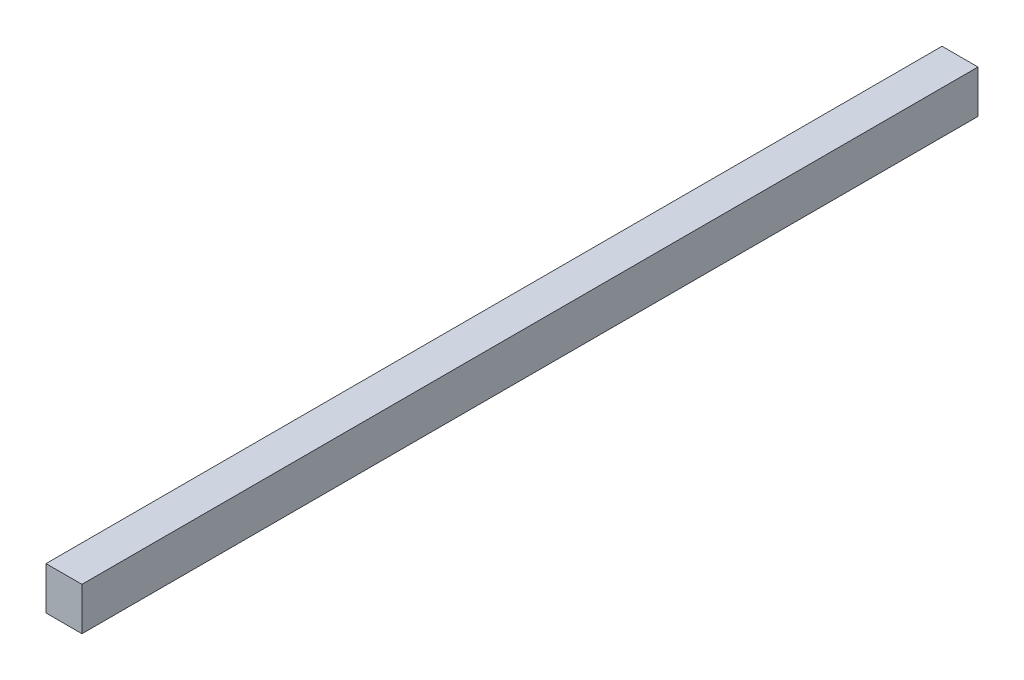
SolidWorks part; units mm, degrees
ref_plane "Front" through (0, 0, 0) normal (0, 0, 1) x (1, 0, 0)
ref_plane "Top" through (0, 0, 0) normal (0, 1, 0) x (1, 0, 0)
ref_plane "Right" through (0, 0, 0) normal (1, 0, 0) x (0, 0, -1)
sketch "Esquisse1" plane through (0, 0, 0) normal (0, 0, 1) x (1, 0, 0)
  line L1 (0, 0) -> (63, 0)
  line L2 (0, 0) -> (0, 75)
  line L3 (0, 75) -> (63, 75)
  line L4 (63, 0) -> (63, 75)
  dimension "D1" = 75
  dimension "D2" = 63
extrude "Boss.-Extru.1" add sketch "Esquisse1" along normal blind 1570
